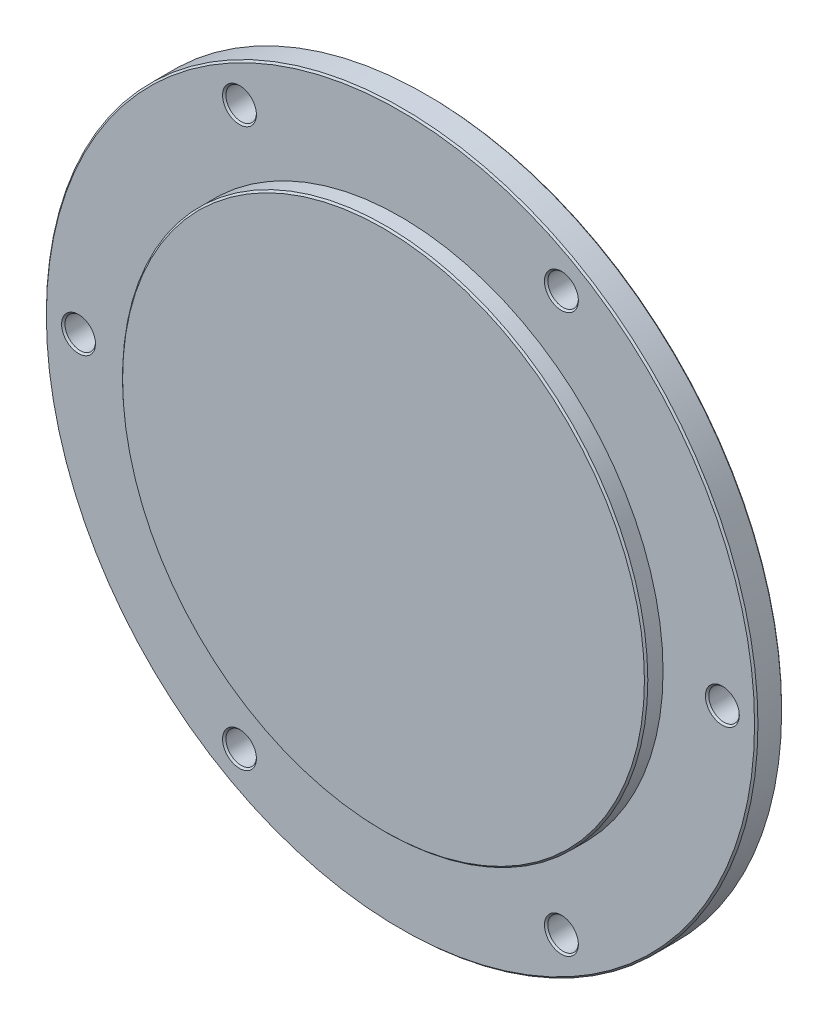
SolidWorks part; units mm, degrees
ref_plane "Front Plane" through (0, 0, 0) normal (0, 0, 1) x (1, 0, 0)
ref_plane "Top Plane" through (0, 0, 0) normal (0, 1, 0) x (1, 0, 0)
ref_plane "Right Plane" through (0, 0, 0) normal (1, 0, 0) x (0, 0, -1)
sketch "Sketch1" plane through (0, 0, 0) normal (0, 1, 0) x (1, 0, 0)
  line L0 (105, 0) -> (0, 0)
  line L1 (0, 0) -> (0, -8)
  line L2 (0, -8) -> (104.5, -8)
  line L3 (104.5, -8) -> (105, -7.5)
  line L4 (105, -7.5) -> (105, 0)
  line L5 (0, 0) -> (0, -8) construction
revolve "Revolve1" add sketch "Sketch1" angle 360 about L5
hole_wizard "Hole1" positions "Sketch3" profile "Sketch2" legacy
sketch "Sketch3" plane through (0, 0, 8) normal (0, 0, 1) x (1, 0, 0)
  point P0 (-47.5, -82.2724)
  point P1 (-47.5, 82.2724)
sketch "Sketch2" plane through (-47.5, -82.2724, 8) normal (1, 0, 0) x (0, -1, 0)
  line L0 (0, 0) -> (0, 8)
  line L1 (0, 8) -> (4.5, 8)
  line L2 (4.5, 8) -> (4.5, 0)
  line L3 (4.5, 0) -> (0, 0)
  line L4 (0, 110) -> (0, -10) construction
  dimension "Diameter" = 9
  dimension "Depth" = 8
hole_wizard "Hole2" positions "Sketch5" profile "Sketch4" legacy
sketch "Sketch5" plane through (0, 0, 0) normal (0, 0, -1) x (-1, 0, 0)
  point P0 (-47.5, -82.2724)
  point P1 (95, 0)
  point P2 (-47.5, 82.2724)
  point P3 (-95, 0)
sketch "Sketch4" plane through (47.5, -82.2724, 0) normal (1, 0, 0) x (0, 1, 0)
  line L0 (0, 0) -> (0, 8)
  line L1 (0, 8) -> (4.5, 8)
  line L2 (4.5, 8) -> (4.5, 0)
  line L3 (4.5, 0) -> (0, 0)
  line L4 (0, 110) -> (0, -10) construction
  dimension "Diameter" = 9
  dimension "Depth" = 8
sketch "Sketch6" plane through (0, 0, 8) normal (0, 0, 1) x (1, 0, 0)
  circle A0 centre (0, 0) radius 77.5
  dimension "D1" = 155
extrude "Boss-Extrude1" add sketch "Sketch6" along normal blind 5
chamfer "Chamfer1" distance 0.5 angle 45 14 edges at (43, -82.2724, 8) (90.5, 0, 8) (-99.5, 0, 8) (-43, -82.2724, 0) (43, -82.2724, 0) (-99.5, 0, 0) (-43, -82.2724, 8) (-43, 82.2724, 0) (43, 82.2724, 8) (43, 82.2724, 0) (105, 0, 0) (90.5, 0, 0) (-43, 82.2724, 8) (77.5, 0, 13)
